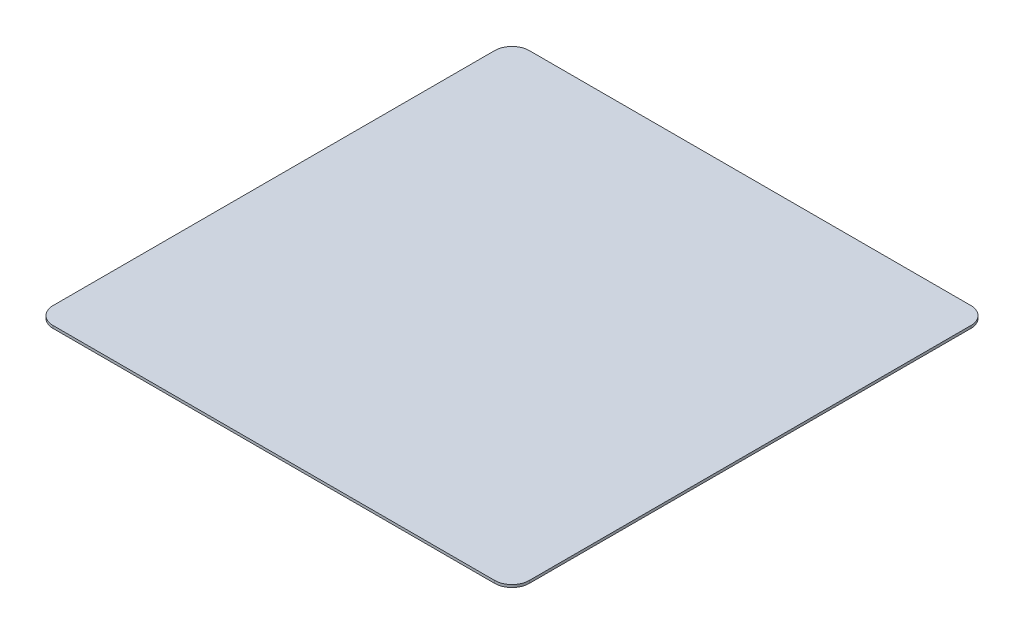
SolidWorks part; units mm, degrees
ref_plane "Front Plane" through (0, 0, 0) normal (0, 0, 1) x (1, 0, 0)
ref_plane "Top Plane" through (0, 0, 0) normal (0, 1, 0) x (1, 0, 0)
ref_plane "Right Plane" through (0, 0, 0) normal (1, 0, 0) x (0, 0, -1)
sketch "Sketch1" plane through (0, 0, 0) normal (0, 1, 0) x (1, 0, 0)
  line L1 (-255, 275) -> (255, 275)
  line L2 (-275, 255) -> (-275, -255)
  line L3 (-255, -275) -> (255, -275)
  line L4 (275, 255) -> (275, -255)
  line L5 (-275, 275) -> (275, -275) construction
  line L6 (-275, -275) -> (275, 275) construction
  arc A0 (-255, -275) -> (-275, -255) centre (-255, -255) cw
  arc A1 (255, -275) -> (275, -255) centre (255, -255) ccw
  arc A2 (275, 255) -> (255, 275) centre (255, 255) ccw
  arc A3 (-255, 275) -> (-275, 255) centre (-255, 255) ccw
  point P0 (0, 0)
  dimension "D3" = 20
  dimension "D1" = 550
  dimension "D2" = 550
extrude "Boss-Extrude1" add sketch "Sketch1" along normal blind 3
equation "\"corner_radius\"= 20mm"
equation "\"hole_spacing\"= 50mm"
equation "\"panel_thickness\"= 3mm"
equation "\"D3@Sketch1\"=\"corner_radius\""
equation "\"D1@Boss-Extrude1\"=\"panel_thickness\""
